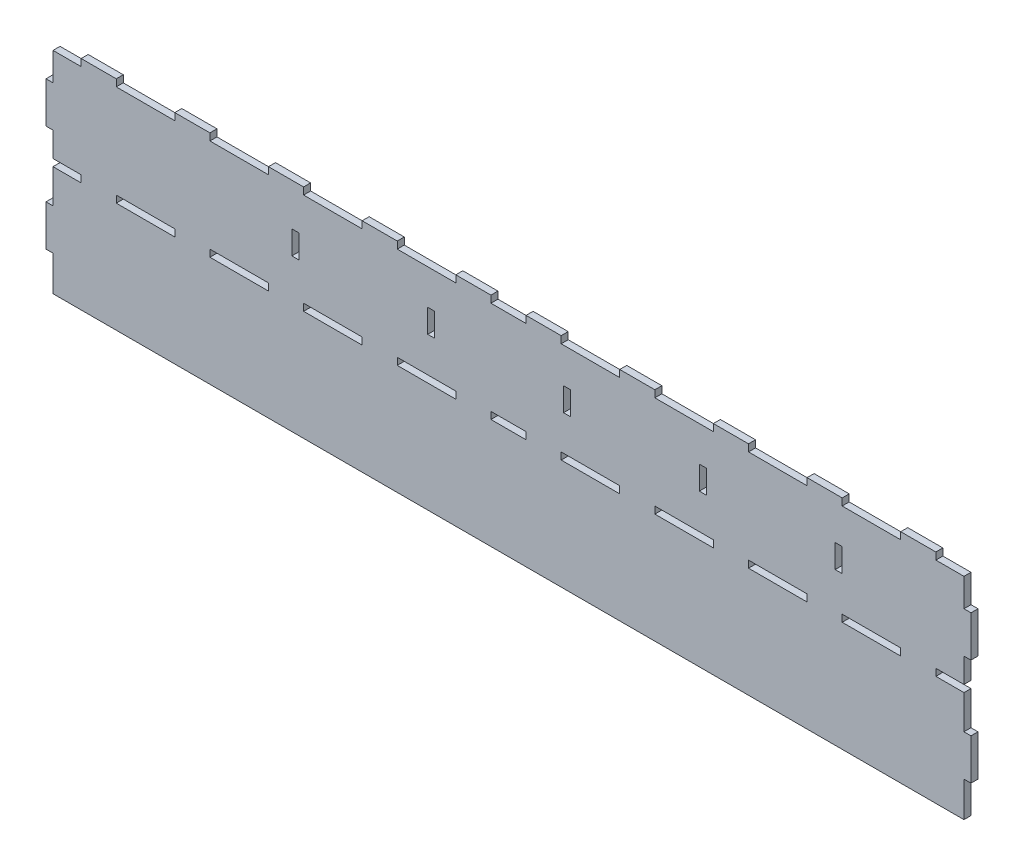
SolidWorks part; units mm, degrees
material "Acrylic (Medium-high impact)"
ref_plane "Front Plane" through (0, 0, 0) normal (0, 0, 1) x (1, 0, 0)
ref_plane "Top Plane" through (0, 0, 0) normal (0, 1, 0) x (1, 0, 0)
ref_plane "Right Plane" through (0, 0, 0) normal (1, 0, 0) x (0, 0, -1)
sketch "Sketch1" plane through (0, 0, 0) normal (0, 0, 1) x (1, 0, 0)
  line L1 (395, 90) -> (-395, 90)
  line L2 (395, 90) -> (395, -90)
  line L3 (395, -90) -> (-395, -90)
  line L4 (-395, 90) -> (-395, -90)
  line L5 (395, 90) -> (-395, -90) construction
  line L6 (395, -90) -> (-395, 90) construction
  point P0 (0, 0)
  dimension "D1" = 790
  dimension "D2" = 180
extrude "Boss-Extrude1" add sketch "Sketch1" along normal blind 6
sketch "Sketch2" plane through (0, 0, 6) normal (0, 0, 1) x (1, 0, 0)
  line L0 (0, 0) -> (0, 150.7771) construction
  line L1 (175, 10) -> (125, 10)
  line L2 (125, 10) -> (125, 4)
  line L3 (125, 4) -> (175, 4)
  line L4 (15, 10) -> (-15, 10)
  line L5 (-15, 10) -> (-15, 4)
  line L6 (-15, 4) -> (15, 4)
  line L7 (15, 4) -> (15, 10)
  line L8 (15, 10) -> (-15, 10)
  line L9 (-15, 10) -> (-15, 4)
  line L10 (-15, 4) -> (15, 4)
  line L11 (15, 4) -> (15, 10)
  line L12 (95, 10) -> (45, 10)
  line L13 (45, 10) -> (45, 4)
  line L14 (45, 4) -> (95, 4)
  line L15 (95, 4) -> (95, 10)
  line L16 (95, 10) -> (45, 10)
  line L17 (45, 10) -> (45, 4)
  line L18 (45, 4) -> (95, 4)
  line L19 (95, 4) -> (95, 10)
  line L20 (175, 4) -> (175, 10)
  line L21 (255, 10) -> (205, 10)
  line L22 (205, 10) -> (205, 4)
  line L23 (205, 4) -> (255, 4)
  line L24 (255, 4) -> (255, 10)
  line L25 (335, 10) -> (285, 10)
  line L26 (285, 10) -> (285, 4)
  line L27 (285, 4) -> (335, 4)
  line L28 (335, 4) -> (335, 10)
  line L29 (415, 10) -> (365, 10)
  line L30 (365, 10) -> (365, 4)
  line L31 (365, 4) -> (415, 4)
  line L32 (415, 4) -> (415, 10)
  line L33 (-415, 4) -> (-415, 10)
  line L34 (-365, 4) -> (-415, 4)
  line L35 (-365, 10) -> (-365, 4)
  line L36 (-415, 10) -> (-365, 10)
  line L37 (-335, 4) -> (-335, 10)
  line L38 (-285, 4) -> (-335, 4)
  line L39 (-285, 10) -> (-285, 4)
  line L40 (-335, 10) -> (-285, 10)
  line L41 (-255, 4) -> (-255, 10)
  line L42 (-205, 4) -> (-255, 4)
  line L43 (-205, 10) -> (-205, 4)
  line L44 (-255, 10) -> (-205, 10)
  line L45 (-175, 4) -> (-175, 10)
  line L46 (-95, 4) -> (-95, 10)
  line L47 (-45, 4) -> (-95, 4)
  line L48 (-45, 10) -> (-45, 4)
  line L49 (-95, 10) -> (-45, 10)
  line L50 (-125, 4) -> (-175, 4)
  line L51 (-125, 10) -> (-125, 4)
  line L52 (-175, 10) -> (-125, 10)
  dimension "D1" = 0
  dimension "D2" = 0
  dimension "D3" = 5
extrude "Cut-Extrude1" cut sketch "Sketch2" against normal blind 10
sketch "Sketch3" plane through (0, 0, 6) normal (0, 0, 1) x (1, 0, 0)
  line L0 (-69, 40) -> (-63, 40)
  line L1 (-63, 40) -> (-63, 60)
  line L2 (-63, 60) -> (-69, 60)
  line L3 (-69, 60) -> (-69, 40)
  line L4 (-185, 40) -> (-179, 40)
  line L5 (-179, 40) -> (-179, 60)
  line L6 (-179, 60) -> (-185, 60)
  line L7 (-185, 60) -> (-185, 40)
  line L8 (-185, 40) -> (-179, 40)
  line L9 (-179, 40) -> (-179, 60)
  line L10 (-179, 60) -> (-185, 60)
  line L11 (-185, 60) -> (-185, 40)
  line L12 (47, 40) -> (53, 40)
  line L13 (53, 40) -> (53, 60)
  line L14 (53, 60) -> (47, 60)
  line L15 (47, 60) -> (47, 40)
  line L16 (163, 40) -> (169, 40)
  line L17 (169, 40) -> (169, 60)
  line L18 (169, 60) -> (163, 60)
  line L19 (163, 60) -> (163, 40)
  line L20 (279, 40) -> (285, 40)
  line L21 (285, 40) -> (285, 60)
  line L22 (285, 60) -> (279, 60)
  line L23 (279, 60) -> (279, 40)
  dimension "D1" = 0
  dimension "D2" = 5
extrude "Cut-Extrude2" cut sketch "Sketch3" against normal blind 10
sketch "Sketch4" plane through (0, 0, 6) normal (0, 0, 1) x (1, 0, 0)
  line L3 (125, 96) -> (95, 96)
  line L4 (95, 96) -> (95, 90)
  line L5 (95, 90) -> (125, 90)
  line L6 (125, 90) -> (125, 96)
  line L7 (45, 96) -> (15, 96)
  line L8 (15, 96) -> (15, 90)
  line L9 (15, 90) -> (45, 90)
  line L10 (45, 90) -> (45, 96)
  line L11 (45, 96) -> (15, 96)
  line L12 (15, 96) -> (15, 90)
  line L13 (15, 90) -> (45, 90)
  line L14 (45, 90) -> (45, 96)
  line L15 (205, 96) -> (175, 96)
  line L16 (175, 96) -> (175, 90)
  line L17 (175, 90) -> (205, 90)
  line L18 (205, 90) -> (205, 96)
  line L19 (285, 96) -> (255, 96)
  line L20 (255, 96) -> (255, 90)
  line L21 (255, 90) -> (285, 90)
  line L22 (285, 90) -> (285, 96)
  line L23 (365, 96) -> (335, 96)
  line L24 (335, 96) -> (335, 90)
  line L25 (335, 90) -> (365, 90)
  line L26 (365, 90) -> (365, 96)
  line L27 (-365, 90) -> (-365, 96)
  line L28 (0, 0) -> (0, 214.9744) construction
  line L30 (-335, 90) -> (-365, 90)
  line L31 (-335, 96) -> (-335, 90)
  line L32 (-365, 96) -> (-335, 96)
  line L33 (-285, 90) -> (-285, 96)
  line L34 (-255, 90) -> (-285, 90)
  line L35 (-255, 96) -> (-255, 90)
  line L36 (-285, 96) -> (-255, 96)
  line L37 (-205, 90) -> (-205, 96)
  line L38 (-175, 90) -> (-205, 90)
  line L39 (-175, 96) -> (-175, 90)
  line L40 (-205, 96) -> (-175, 96)
  line L41 (-45, 90) -> (-45, 96)
  line L42 (-15, 90) -> (-45, 90)
  line L43 (-15, 96) -> (-15, 90)
  line L44 (-45, 96) -> (-15, 96)
  line L45 (-125, 90) -> (-125, 96)
  line L46 (-95, 90) -> (-125, 90)
  line L47 (-95, 96) -> (-95, 90)
  line L48 (-125, 96) -> (-95, 96)
  dimension "D1" = 0
extrude "Boss-Extrude2" add sketch "Sketch4" against normal blind 6
sketch "Sketch5" plane through (0, 0, 6) normal (0, 0, 1) x (1, 0, 0)
  line L0 (389, 96) -> (389, 66) construction
  line L1 (395, -90) -> (389, -90)
  line L2 (395, -90) -> (395, -60)
  line L3 (395, -60) -> (389, -60)
  line L4 (389, -90) -> (389, -60)
  line L5 (365, 96) -> (335, 96) construction
  line L6 (395, 4) -> (389, 4)
  line L7 (395, 4) -> (395, -25)
  line L8 (395, -25) -> (389, -25)
  line L9 (389, 4) -> (389, -25)
  line L10 (395, 90) -> (389, 90)
  line L11 (395, 90) -> (395, 66)
  line L12 (395, 66) -> (389, 66)
  line L13 (389, 90) -> (389, 66)
  line L14 (395, 10) -> (389, 10)
  line L15 (395, 10) -> (395, 31)
  line L16 (395, 31) -> (389, 31)
  line L17 (389, 10) -> (389, 31)
  line L18 (0, 0) -> (0, -164.0937) construction
  line L19 (-389, 10) -> (-389, 31)
  line L20 (-395, 31) -> (-389, 31)
  line L21 (-395, 10) -> (-395, 31)
  line L22 (-395, 10) -> (-389, 10)
  line L23 (-389, 90) -> (-389, 66)
  line L24 (-395, 66) -> (-389, 66)
  line L25 (-395, 90) -> (-395, 66)
  line L26 (-395, 90) -> (-389, 90)
  line L27 (-389, 4) -> (-389, -25)
  line L28 (-395, -25) -> (-389, -25)
  line L29 (-395, 4) -> (-395, -25)
  line L30 (-395, 4) -> (-389, 4)
  line L31 (-389, -90) -> (-389, -60)
  line L32 (-395, -60) -> (-389, -60)
  line L33 (-395, -90) -> (-395, -60)
  line L34 (-395, -90) -> (-389, -90)
  dimension "D1" = 30
  dimension "D2" = 30
  dimension "D3" = 35
  dimension "D4" = 35
extrude "Cut-Extrude3" cut sketch "Sketch5" against normal blind 6
